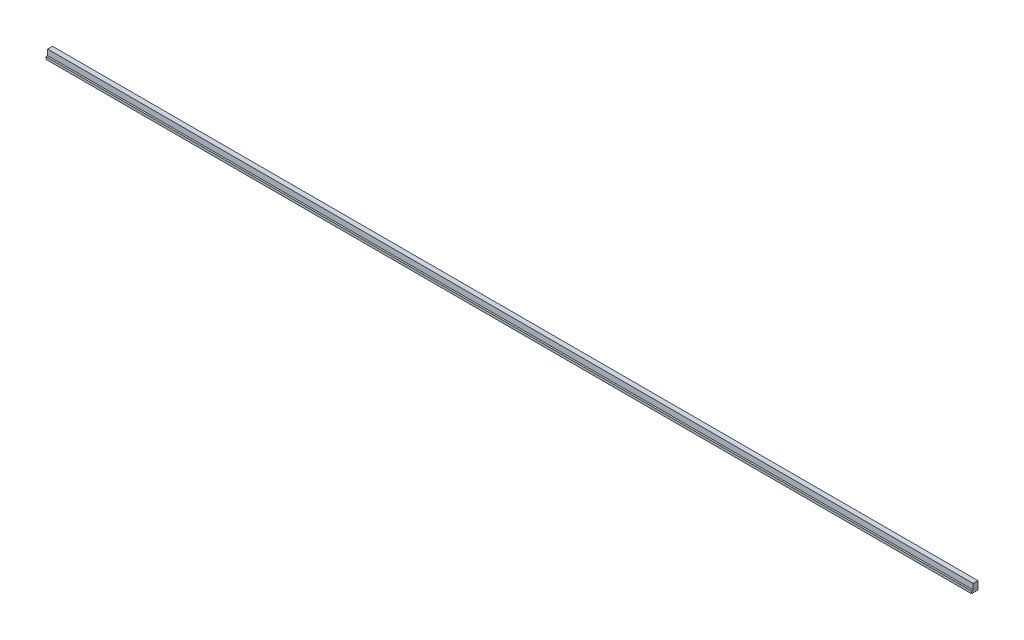
SolidWorks part; units mm, degrees
ref_plane "前视基准面" through (0, 0, 0) normal (0, 0, 1) x (1, 0, 0)
ref_plane "上视基准面" through (0, 0, 0) normal (0, 1, 0) x (1, 0, 0)
ref_plane "右视基准面" through (0, 0, 0) normal (1, 0, 0) x (0, 0, -1)
sketch "草图1" plane through (0, 0, 0) normal (0, 0, 1) x (1, 0, 0)
  line L1 (-2850, 25) -> (2850, 25)
  line L2 (-2850, 25) -> (-2850, -25)
  line L3 (-2850, -25) -> (2850, -25)
  line L4 (2850, 25) -> (2850, -25)
  line L5 (-2850, 25) -> (2850, -25) construction
  line L6 (-2850, -25) -> (2850, 25) construction
  point P0 (0, 0)
  dimension "D1" = 50
  dimension "D2" = 5700
extrude "凸台-拉伸1" add sketch "草图1" along normal mid plane 30
sketch "草图3" plane through (0, 0, 15) normal (0, 0, 1) x (1, 0, 0)
  line L0 (2850, -25) -> (2850, 25) construction
  line L1 (-2850, -25) -> (2850, -25)
  line L2 (-2850, -25) -> (-2850, -10)
  line L3 (-2850, -10) -> (2850, -10)
  line L4 (2850, -25) -> (2850, -10)
  dimension "D1" = 15
extrude "凸台-拉伸3" add sketch "草图3" along normal blind 10
equation "\"零件重量\"= \"SW-质量\""
